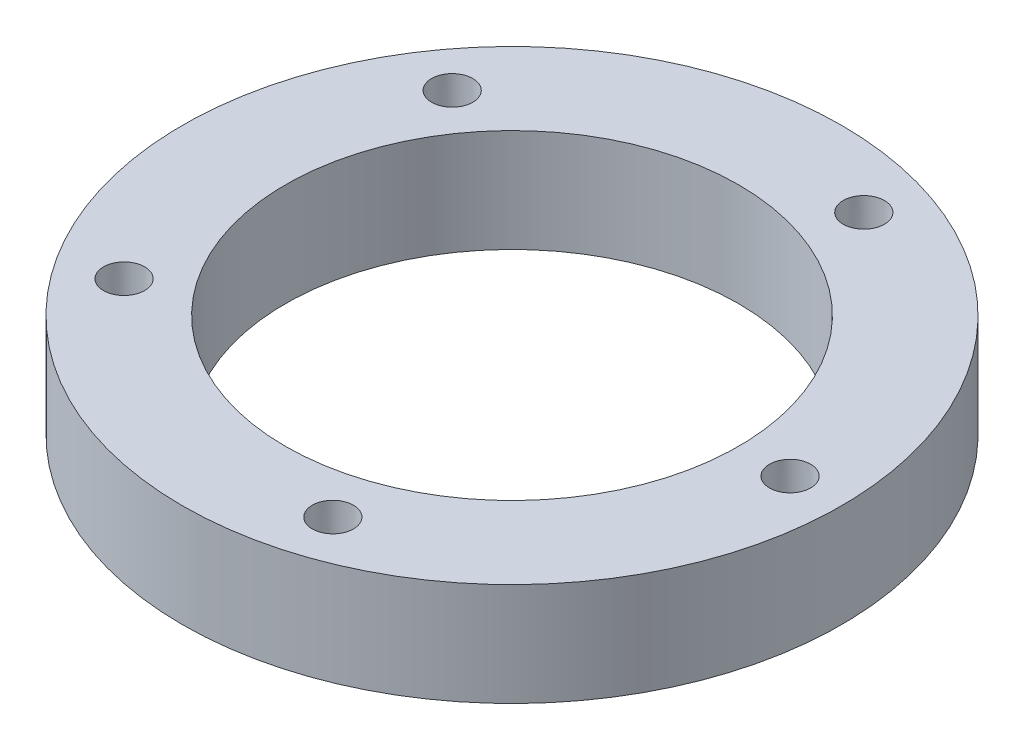
SolidWorks part; units mm, degrees
ref_plane "Front Plane" through (0, 0, 0) normal (0, 0, 1) x (1, 0, 0)
ref_plane "Top Plane" through (0, 0, 0) normal (0, 1, 0) x (1, 0, 0)
ref_plane "Right Plane" through (0, 0, 0) normal (1, 0, 0) x (0, 0, -1)
sketch "Sketch1" plane through (0, 0, 0) normal (0, 1, 0) x (1, 0, 0)
  circle A0 centre (0, 0) radius 11
  circle A1 centre (0, 0) radius 16
  dimension "D1" = 22
  dimension "D2" = 5
extrude "Boss-Extrude2" add sketch "Sketch1" along normal blind 5
sketch "Sketch2" plane through (0, 5, 0) normal (0, 1, 0) x (1, 0, 0)
  line L0 (-11, 0) -> (-16, 0) construction
  line L1 (-12.5, 0.9943) -> (-12.5, -1.1473) construction
  line L2 (-0.0114, 0.0405) -> (12.5008, 0.0405) construction
  circle A0 centre (0, 0) radius 11 construction
  circle A1 centre (0, 0) radius 16 construction
  arc A2 (-11.4427, 7.1634) -> (-11.5211, -7.0367) centre (0, 0) ccw
  circle A3 centre (13.5, 0) radius 1
  circle A4 centre (4.1254, -12.8221) radius 1
  circle A5 centre (-10.9661, -7.8686) radius 1
  circle A6 centre (-10.9185, 8.015) radius 1
  circle A7 centre (4.2024, 12.8781) radius 1
  arc A8 (3.2292, 13.1081) -> (-10.2631, 8.7703) centre (0, 0) ccw
  arc A9 (13.463, 0.9993) -> (5.1239, 12.4898) centre (0, 0) ccw
  arc A10 (5.0753, -12.5097) -> (13.463, -0.9993) centre (0, 0) ccw
  arc A11 (-10.3558, -8.6607) -> (3.1714, -13.1222) centre (0, 0) ccw
  dimension "D1" = 2
  dimension "D3" = 2.5
  dimension "D2" = 5
extrude "Cut-Extrude1" cut sketch "Sketch2" against normal blind 5 draft 2 contours A6 | A5 | A4 | A3 | A7
equation "\"outer-diameter\"= 20"
equation "\"screw-diameter\"= 2"
equation "\"bearing-thickness\"= 5"
